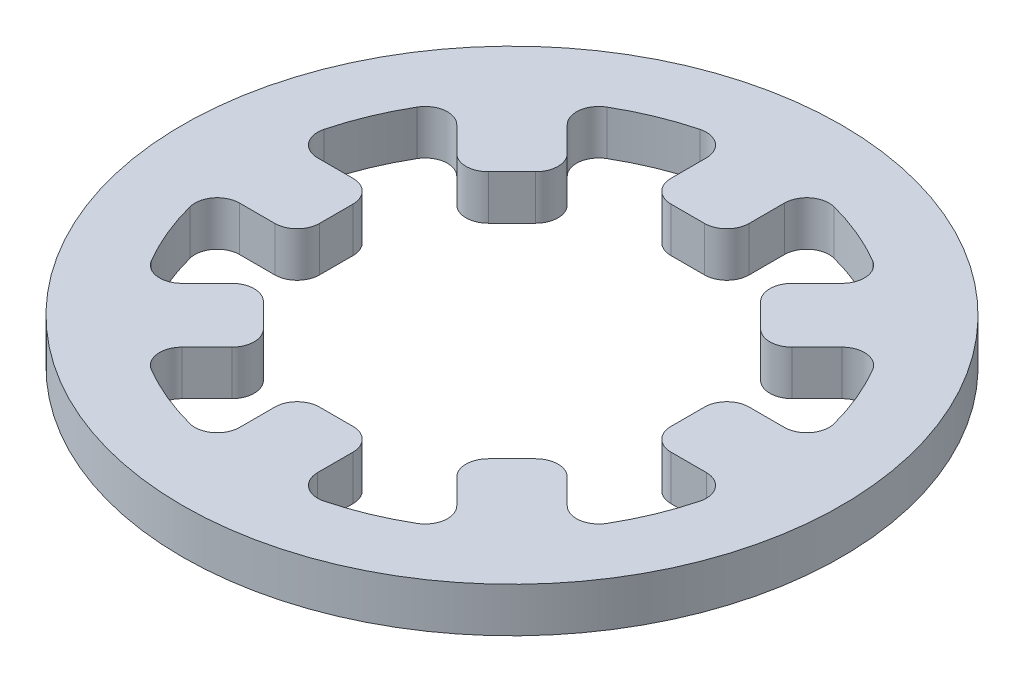
SolidWorks part; units mm, degrees
material "Plain Carbon Steel"
ref_plane "Front Plane" through (0, 0, 0) normal (0, 0, 1) x (1, 0, 0)
ref_plane "Top Plane" through (0, 0, 0) normal (0, 1, 0) x (1, 0, 0)
ref_plane "Right Plane" through (0, 0, 0) normal (1, 0, 0) x (0, 0, -1)
sketch "Sketch1" plane through (0, 0, 0) normal (0, 1, 0) x (1, 0, 0)
  line L0 (-0.889, 5.3114) -> (-0.889, 4.508)
  line L1 (-0.381, 4) -> (0.381, 4)
  line L2 (0.889, 4.508) -> (0.889, 5.3114)
  line L3 (3.1271, 4.3843) -> (2.559, 3.8163)
  line L4 (3.8163, 2.559) -> (4.3843, 3.1271)
  line L5 (2.559, 3.0978) -> (3.0978, 2.559)
  line L6 (5.3114, 0.889) -> (4.508, 0.889)
  line L7 (4.508, -0.889) -> (5.3114, -0.889)
  line L8 (4, 0.381) -> (4, -0.381)
  line L9 (4.3843, -3.1271) -> (3.8163, -2.559)
  line L10 (2.559, -3.8163) -> (3.1271, -4.3843)
  line L11 (3.0978, -2.559) -> (2.559, -3.0978)
  line L12 (0.889, -5.3114) -> (0.889, -4.508)
  line L13 (-0.889, -4.508) -> (-0.889, -5.3114)
  line L14 (0.381, -4) -> (-0.381, -4)
  line L15 (-3.1271, -4.3843) -> (-2.559, -3.8163)
  line L16 (-3.8163, -2.559) -> (-4.3843, -3.1271)
  line L17 (-2.559, -3.0978) -> (-3.0978, -2.559)
  line L18 (-5.3114, -0.889) -> (-4.508, -0.889)
  line L19 (-4.508, 0.889) -> (-5.3114, 0.889)
  line L20 (-4, -0.381) -> (-4, 0.381)
  line L21 (-4.3843, 3.1271) -> (-3.8163, 2.559)
  line L22 (-2.559, 3.8163) -> (-3.1271, 4.3843)
  line L23 (-3.0978, 2.559) -> (-2.559, 3.0978)
  circle A0 centre (0, 0) radius 7.5
  arc A1 (-1.5262, 5.8026) -> (-3.0239, 5.1823) centre (0, 0) ccw
  arc A2 (-5.1823, 3.0239) -> (-5.8026, 1.5262) centre (0, 0) ccw
  arc A3 (-5.8026, -1.5262) -> (-5.1823, -3.0239) centre (0, 0) ccw
  arc A4 (-3.0239, -5.1823) -> (-1.5262, -5.8026) centre (0, 0) ccw
  arc A5 (1.5262, -5.8026) -> (3.0239, -5.1823) centre (0, 0) ccw
  arc A6 (5.1823, -3.0239) -> (5.8026, -1.5262) centre (0, 0) ccw
  arc A7 (5.8026, 1.5262) -> (5.1823, 3.0239) centre (0, 0) ccw
  arc A8 (3.0239, 5.1823) -> (1.5262, 5.8026) centre (0, 0) ccw
  arc A9 (-3.1271, 4.3843) -> (-3.0239, 5.1823) centre (-2.7679, 4.7435) cw
  arc A10 (-2.559, 3.8163) -> (-2.559, 3.0978) centre (-2.9182, 3.457) cw
  arc A11 (-3.8163, 2.559) -> (-3.0978, 2.559) centre (-3.457, 2.9182) ccw
  arc A12 (-4.3843, 3.1271) -> (-5.1823, 3.0239) centre (-4.7435, 2.7679) ccw
  arc A13 (-5.3114, 0.889) -> (-5.8026, 1.5262) centre (-5.3114, 1.397) cw
  arc A14 (-4.508, 0.889) -> (-4, 0.381) centre (-4.508, 0.381) cw
  arc A15 (-4.508, -0.889) -> (-4, -0.381) centre (-4.508, -0.381) ccw
  arc A16 (-5.3114, -0.889) -> (-5.8026, -1.5262) centre (-5.3114, -1.397) ccw
  arc A17 (-4.3843, -3.1271) -> (-5.1823, -3.0239) centre (-4.7435, -2.7679) cw
  arc A18 (-3.8163, -2.559) -> (-3.0978, -2.559) centre (-3.457, -2.9182) cw
  arc A19 (-2.559, -3.8163) -> (-2.559, -3.0978) centre (-2.9182, -3.457) ccw
  arc A20 (-3.1271, -4.3843) -> (-3.0239, -5.1823) centre (-2.7679, -4.7435) ccw
  arc A21 (-0.889, -5.3114) -> (-1.5262, -5.8026) centre (-1.397, -5.3114) cw
  arc A22 (-0.889, -4.508) -> (-0.381, -4) centre (-0.381, -4.508) cw
  arc A23 (0.889, -4.508) -> (0.381, -4) centre (0.381, -4.508) ccw
  arc A24 (0.889, -5.3114) -> (1.5262, -5.8026) centre (1.397, -5.3114) ccw
  arc A25 (3.1271, -4.3843) -> (3.0239, -5.1823) centre (2.7679, -4.7435) cw
  arc A26 (2.559, -3.8163) -> (2.559, -3.0978) centre (2.9182, -3.457) cw
  arc A27 (3.8163, -2.559) -> (3.0978, -2.559) centre (3.457, -2.9182) ccw
  arc A28 (4.3843, -3.1271) -> (5.1823, -3.0239) centre (4.7435, -2.7679) ccw
  arc A29 (5.3114, -0.889) -> (5.8026, -1.5262) centre (5.3114, -1.397) cw
  arc A30 (4.508, -0.889) -> (4, -0.381) centre (4.508, -0.381) cw
  arc A31 (4.508, 0.889) -> (4, 0.381) centre (4.508, 0.381) ccw
  arc A32 (5.3114, 0.889) -> (5.8026, 1.5262) centre (5.3114, 1.397) ccw
  arc A33 (4.3843, 3.1271) -> (5.1823, 3.0239) centre (4.7435, 2.7679) cw
  arc A34 (3.8163, 2.559) -> (3.0978, 2.559) centre (3.457, 2.9182) cw
  arc A35 (2.559, 3.8163) -> (2.559, 3.0978) centre (2.9182, 3.457) ccw
  arc A36 (3.1271, 4.3843) -> (3.0239, 5.1823) centre (2.7679, 4.7435) ccw
  arc A37 (0.889, 5.3114) -> (1.5262, 5.8026) centre (1.397, 5.3114) cw
  arc A38 (0.381, 4) -> (0.889, 4.508) centre (0.381, 4.508) ccw
  arc A39 (-0.889, 4.508) -> (-0.381, 4) centre (-0.381, 4.508) ccw
  arc A40 (-0.889, 5.3114) -> (-1.5262, 5.8026) centre (-1.397, 5.3114) ccw
  point P8 (-2.2686, 2.3815)
  point P9 (0, 0)
  point P39 (0, 0)
  point P98 (0.889, 4)
  point P101 (-0.889, 4)
  dimension "D1" = 15
  dimension "D2" = 12
  dimension "D6" = 0.508
  dimension "D3" = 4
  dimension "D4" = 1.778
  dimension "D5" = 8
extrude "Boss-Extrude1" add sketch "Sketch1" along normal blind 1.016
